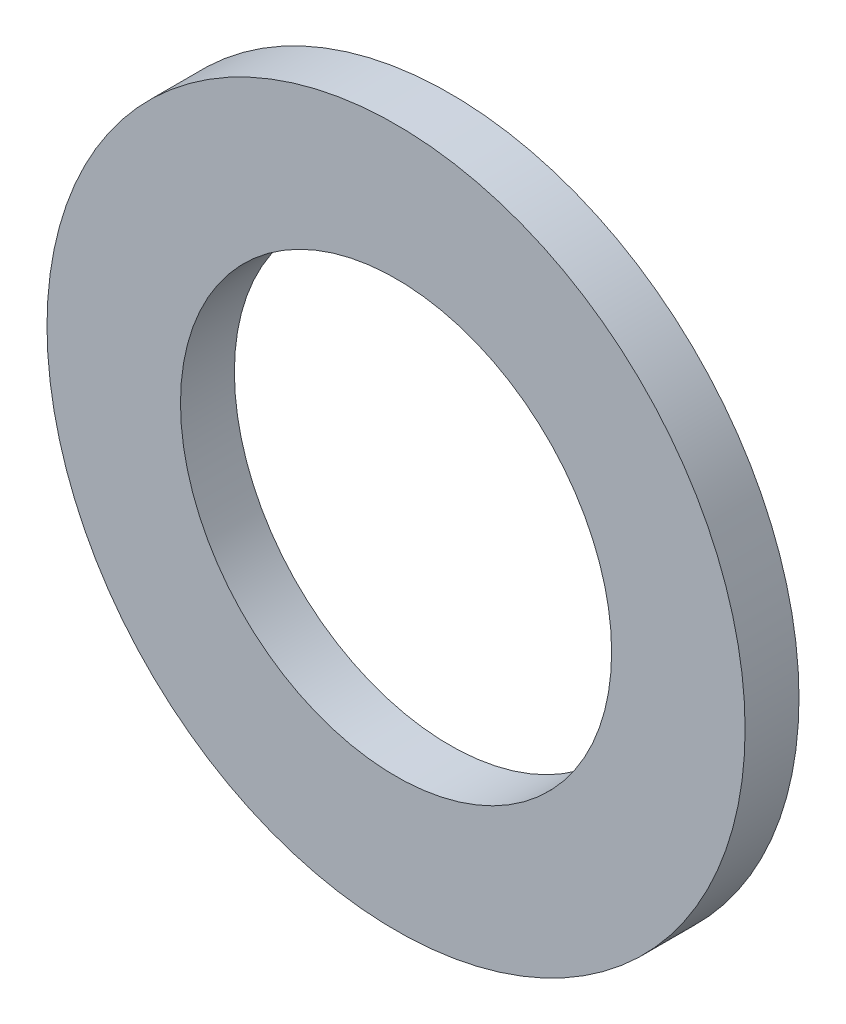
SolidWorks part; units mm, degrees
ref_plane "Front Plane" through (0, 0, 0) normal (0, 0, 1) x (1, 0, 0)
ref_plane "Top Plane" through (0, 0, 0) normal (0, 1, 0) x (1, 0, 0)
ref_plane "Right Plane" through (0, 0, 0) normal (1, 0, 0) x (0, 0, -1)
sketch "Sketch1" plane through (0, 0, 0) normal (0, 0, 1) x (1, 0, 0)
  circle A0 centre (-26.0075, -4.9686) radius 20 construction
  circle A1 centre (-26.0075, -4.9686) radius 20
  circle A2 centre (-26.0075, -4.9686) radius 32.3846
extrude "Boss-Extrude1" add sketch "Sketch1" along normal blind 5
